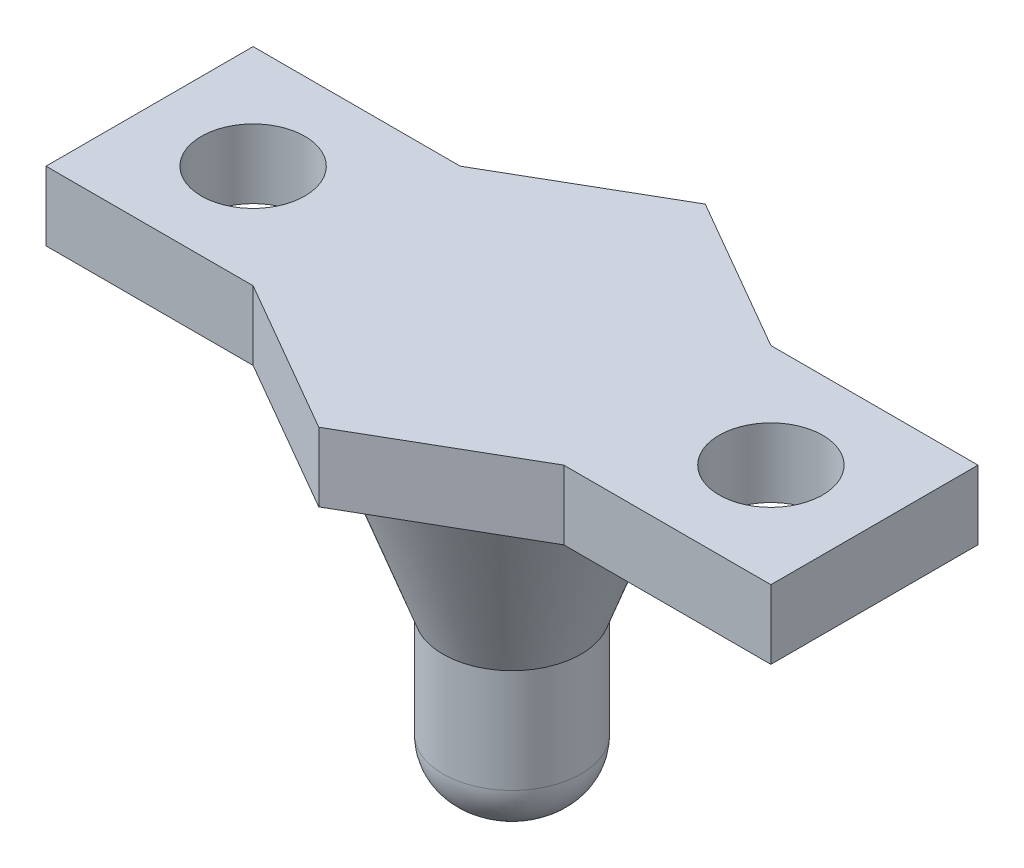
SolidWorks part; units mm, degrees
ref_plane "Front Plane" through (0, 0, 0) normal (0, 0, 1) x (1, 0, 0)
ref_plane "Top Plane" through (0, 0, 0) normal (0, 1, 0) x (1, 0, 0)
ref_plane "Right Plane" through (0, 0, 0) normal (1, 0, 0) x (0, 0, -1)
sketch "Sketch1" plane through (0, 0, 0) normal (0, 1, 0) x (1, 0, 0)
  line L0 (-7.5, 0) -> (0, 0) construction
  line L1 (-4.5, 3) -> (0, 5.5981)
  line L2 (-4.5, -3) -> (-10.5, -3)
  line L4 (-4.5, 3) -> (-10.5, 3)
  line L5 (-10.5, -3) -> (-10.5, 3)
  line L6 (-4.5, -3) -> (-10.5, 3) construction
  line L7 (-4.5, 3) -> (-10.5, -3) construction
  line L8 (-4.5, -3) -> (0, -5.5981)
  line L9 (0, 5.5981) -> (0, 0) construction
  line L10 (4.5, -3) -> (0, -5.5981)
  line L11 (4.5, -3) -> (10.5, -3)
  line L12 (10.5, -3) -> (10.5, 3)
  line L13 (4.5, 3) -> (10.5, 3)
  line L14 (4.5, 3) -> (0, 5.5981)
  circle A0 centre (-7.5, 0) radius 1.5
  circle A1 centre (7.5, 0) radius 1.5
  dimension "D2" = 3
  dimension "D1" = 7.5
  dimension "D3" = 6
  dimension "D4" = 6
  dimension "D5" = 30
  dimension "D6" = 30
extrude "Boss-Extrude1" add sketch "Sketch1" along normal blind 2
sketch "Sketch2" plane through (0, 0, 0) normal (0, 0, 1) x (1, 0, 0)
  line L0 (0, 2) -> (0, -10)
  line L1 (0, -10) -> (0.5, -10)
  line L2 (2, -8.5) -> (2, 2)
  line L3 (0, 2) -> (4.5, 2) construction
  line L4 (2, 2) -> (0, 2)
  line L5 (2, -5.495) -> (4, 0)
  line L6 (0, 0) -> (4.5, 0) construction
  line L7 (4, 0) -> (2, 0)
  arc A0 (0.5, -10) -> (2, -8.5) centre (0.5, -8.5) ccw
  point P11 (2, -10)
  dimension "D3" = 1.5
  dimension "D1" = 12
  dimension "D2" = 2
  dimension "D4" = 2
  dimension "D5" = 70
revolve "Revolve1" add sketch "Sketch2" angle 360 about L0
